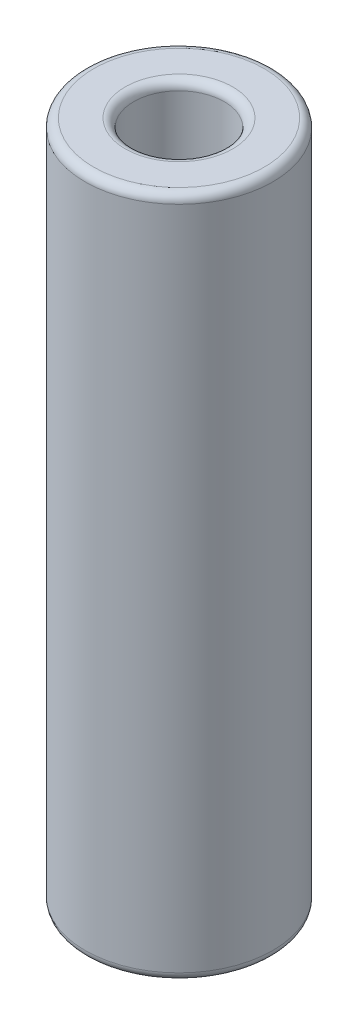
SolidWorks part; units mm, degrees
ref_plane "Plano frontal" through (0, 0, 0) normal (0, 0, 1) x (1, 0, 0)
ref_plane "Plano superior" through (0, 0, 0) normal (0, 1, 0) x (1, 0, 0)
ref_plane "Plano direito" through (0, 0, 0) normal (1, 0, 0) x (0, 0, -1)
sketch "Esboço1" plane through (0, 0, 0) normal (0, 1, 0) x (1, 0, 0)
  circle A0 centre (0, 0) radius 5.5
  dimension "D1" = 11
extrude "Ressalto-extrusão1" add sketch "Esboço1" along normal blind 40
sketch "Esboço2" plane through (0, 40, 0) normal (0, 1, 0) x (1, 0, 0)
  circle A0 centre (0, 0) radius 2.65
  dimension "D1" = 5.3
extrude "Corte-extrusão1" cut sketch "Esboço2" against normal blind 40
fillet "Filete1" radius 0.5 2 edges at (0, 0, 5.5) (0, 40, 5.5)
fillet "Filete2" radius 0.5 2 edges at (0, 40, 2.65) (0, 0, 2.65)
